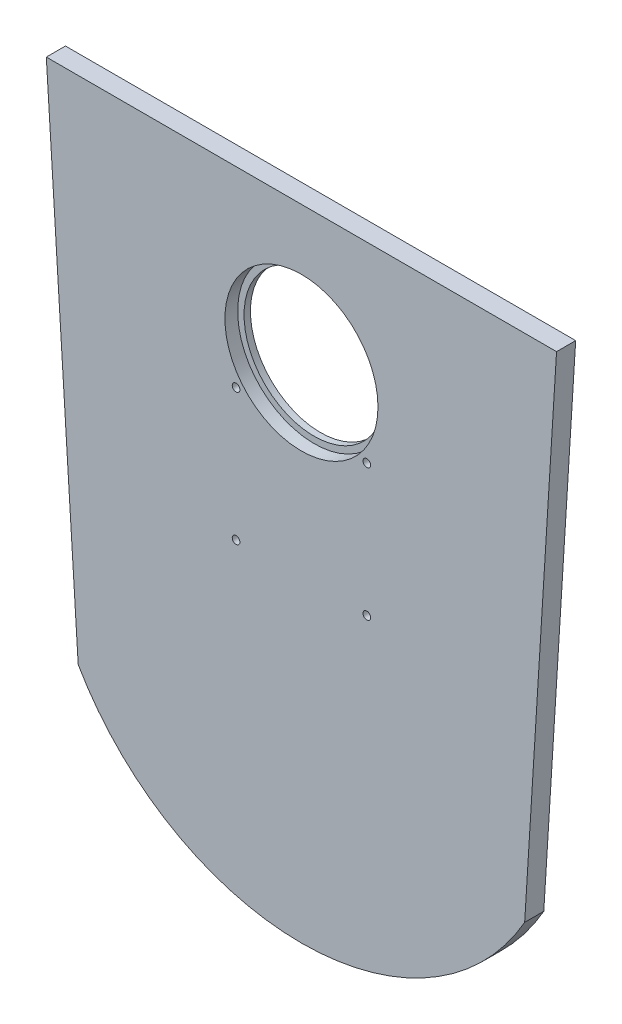
SolidWorks part; units mm, degrees
ref_plane "前视基准面" through (0, 0, 0) normal (0, 0, 1) x (1, 0, 0)
ref_plane "上视基准面" through (0, 0, 0) normal (0, 1, 0) x (1, 0, 0)
ref_plane "右视基准面" through (0, 0, 0) normal (1, 0, 0) x (0, 0, -1)
other "Configuration Table"
sketch "草图1" plane through (0, 0, 0) normal (0, 0, 1) x (1, 0, 0)
  line L1 (0, 0) -> (70, 0)
  line L2 (0, 0) -> (0, 80)
  line L3 (0, 80) -> (70, 80)
  line L4 (70, 0) -> (70, 80)
  dimension "D1" = 70
  dimension "D2" = 80
extrude "凸台-拉伸1" add sketch "草图1" along normal blind 3
sketch "草图2" plane through (0, 0, 3) normal (0, 0, 1) x (1, 0, 0)
  line L0 (35, 40) -> (35, -49960) construction
  line L1 (70, 80) -> (0, 80) construction
  line L3 (24.75, 50) -> (45.25, 50) construction
  line L4 (24.75, 50) -> (24.75, 29.3) construction
  line L5 (24.75, 29.3) -> (45.25, 29.3) construction
  line L6 (45.25, 50) -> (45.25, 29.3) construction
  circle A0 centre (24.75, 50) radius 0.6
  circle A1 centre (45.25, 50) radius 0.6
  circle A2 centre (45.25, 29.3) radius 0.6
  circle A3 centre (24.75, 29.3) radius 0.6
  circle A4 centre (35, 58.5) radius 11
  point P4 (35, 80)
  point P9 (35, 50)
  point P16 (25, 63.4164)
  dimension "D3" = 1.2
  dimension "D4" = 1.2
  dimension "D5" = 1.2
  dimension "D6" = 1.2
  dimension "D8" = 22
  dimension "D1" = 20.5
  dimension "D2" = 20.7
  dimension "D7" = 30
  dimension "D9" = 8.5
extrude "切除-拉伸1" cut sketch "草图2" against normal up to next
sketch "草图3" plane through (0, 0, 3) normal (0, 0, 1) x (1, 0, 0)
  circle A0 centre (35, 58.5) radius 12
  dimension "D1" = 24
extrude "切除-拉伸2" cut sketch "草图3" against normal blind 2
sketch "草图4" plane through (0, 0, 0) normal (0, 0, -1) x (-1, 0, 0)
  line L1 (-11.2132, 43.4394) -> (-1.2132, 43.4394)
  line L2 (-11.2132, 43.4394) -> (-11.2132, 33.4394)
  line L3 (-11.2132, 33.4394) -> (-1.2132, 33.4394)
  line L4 (-1.2132, 43.4394) -> (-1.2132, 33.4394)
  dimension "D1" = 10
  dimension "D2" = 10
extrude "切除-拉伸3" [suppressed] cut sketch "草图4" against normal up to next contours L2 L1 L4 L3
sketch "草图5" plane through (0, 0, 0) normal (0, 0, -1) x (-1, 0, 0)
  line L0 (-35, 0) -> (-35, -50000) construction
  line L1 (0, 0) -> (-70, 0) construction
  line L2 (-70, 0) -> (-75, 80)
  line L3 (-75, 80) -> (-70, 80)
  line L4 (5, 80) -> (0, 80)
  line L5 (0, 0) -> (5, 80)
  line L10 (0, 0) -> (0, 80)
  line L11 (0, 80) -> (-70, 80)
  line L12 (-70, 80) -> (-70, 0)
  line L13 (-70, 0) -> (0, 0)
  line L14 (0, 0) -> (0, 80)
  line L15 (0, 80) -> (-70, 80)
  line L16 (-70, 80) -> (-70, 0)
  line L17 (-70, 0) -> (0, 0)
  arc A0 (-70, 0) -> (0, 0) centre (-35, 20) ccw
  point P4 (-35, 0)
  line M12 (0, 0) -> (0, 80)
  line M14 (-70, 80) -> (-70, 0)
  line M15 (-70, 0) -> (0, 0)
  dimension "D1" = 20
  dimension "D2" = 5
  dimension "D3" = 0
extrude "凸台-拉伸2" add sketch "草图5" against normal up to surface (3 mm away) contours L3 L2 M14 | L5 L4 M12 | L17 L0 A0 | L0 A0 M15 up to face at (47, 58.5, 3)
